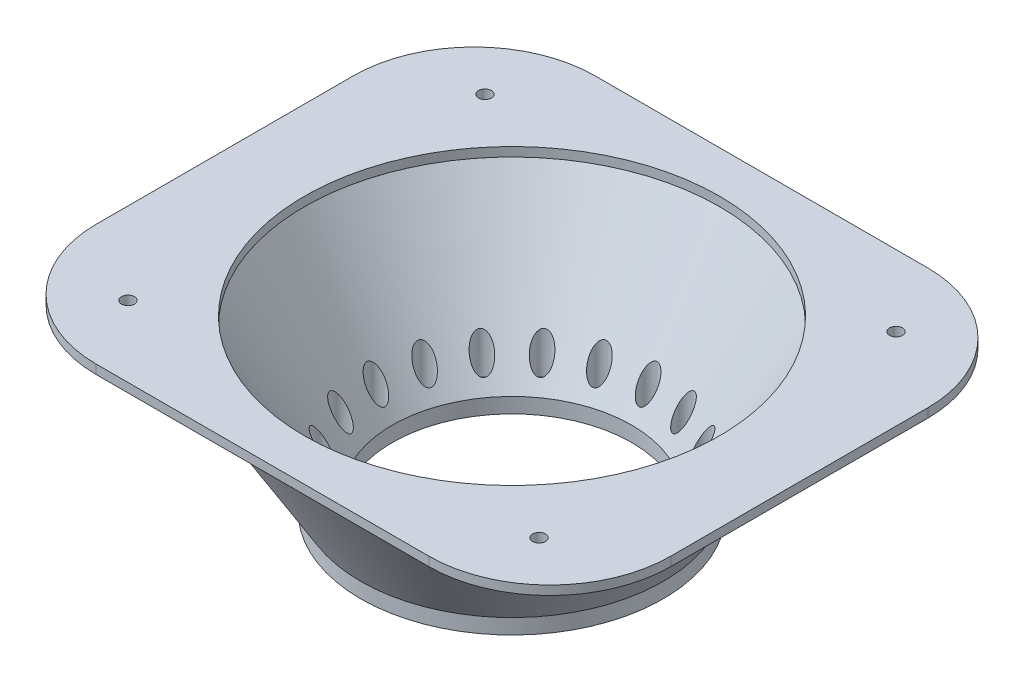
SolidWorks part; units mm, degrees
ref_plane "Front Plane" through (0, 0, 0) normal (0, 0, 1) x (1, 0, 0)
ref_plane "Top Plane" through (0, 0, 0) normal (0, 1, 0) x (1, 0, 0)
ref_plane "Right Plane" through (0, 0, 0) normal (1, 0, 0) x (0, 0, -1)
sketch "Sketch4" plane through (0, 0, 0) normal (0, 1, 0) x (1, 0, 0)
  line L0 (0, -45) -> (0, 45) construction
  line L1 (0, 0) -> (0, -45) construction
  circle A0 centre (0, 0) radius 39.565
  circle A1 centre (0, 0) radius 50
  circle A6 centre (0, -45) radius 1.75
  circle A7 centre (-13.9058, -42.7975) radius 1.75
  circle A8 centre (-26.4503, -36.4058) radius 1.75
  circle A9 centre (-36.4058, -26.4503) radius 1.75
  circle A10 centre (-42.7975, -13.9058) radius 1.75
  circle A11 centre (-45, 0) radius 1.75
  circle A12 centre (-42.7975, 13.9058) radius 1.75
  circle A13 centre (-36.4058, 26.4503) radius 1.75
  circle A14 centre (-26.4503, 36.4058) radius 1.75
  circle A15 centre (-13.9058, 42.7975) radius 1.75
  circle A16 centre (0, 45) radius 1.75
  circle A17 centre (13.9058, 42.7975) radius 1.75
  circle A18 centre (26.4503, 36.4058) radius 1.75
  circle A19 centre (36.4058, 26.4503) radius 1.75
  circle A20 centre (42.7975, 13.9058) radius 1.75
  circle A21 centre (45, 0) radius 1.75
  circle A22 centre (42.7975, -13.9058) radius 1.75
  circle A23 centre (36.4058, -26.4503) radius 1.75
  circle A24 centre (26.4503, -36.4058) radius 1.75
  circle A25 centre (13.9058, -42.7975) radius 1.75
  point P5 (0, 0)
  dimension "D1" = 79.13
  dimension "D3" = 100
  dimension "D5" = 3.5
  dimension "D2" = 90
  dimension "D7" = 45
  dimension "D6" = 20
extrude "Boss-Extrude3" add sketch "Sketch4" along normal blind 5
sketch "Sketch6" plane through (0, 0, 0) normal (1, 0, 0) x (0, 0, -1)
  line L0 (-50, 5) -> (-79.0628, 53)
  line L2 (-50, 5) -> (-39.565, 5)
  line L3 (-39.565, 5) -> (-68.6278, 53)
  line L5 (-68.6278, 53) -> (-79.0628, 53)
  point P3 (0, 0)
  dimension "D1" = 18.6278
  dimension "D2" = 48
ref_plane "Plane1" through (0, 15, 0) normal (0, 1, 0) x (1, 0, 0)
ref_axis "Axis1" through (0, 0, 0) along (0, 1, 0)
revolve "Revolve1" add sketch "Sketch6" angle 360 about axis through (0, 0, 0) along (0, 1, 0)
sketch "Sketch7" plane through (0, 53, 0) normal (0, 1, 0) x (1, 0, 0)
  line L1 (-95, 82.5) -> (95, 82.5)
  line L2 (-95, 82.5) -> (-95, -82.5)
  line L3 (-95, -82.5) -> (95, -82.5)
  line L4 (95, 82.5) -> (95, -82.5)
  line L5 (-95, 82.5) -> (95, -82.5) construction
  line L6 (-95, -82.5) -> (95, 82.5) construction
  circle A0 centre (0, 0) radius 68.6289
  circle A1 centre (-67.953, 59.0118) radius 2.15
  circle A2 centre (67.953, 59.0118) radius 2.15
  circle A3 centre (67.953, -59.0118) radius 2.15
  circle A4 centre (-67.953, -59.0118) radius 2.15
  point P4 (0, 0)
  point P16 (0, 0)
  point P17 (0, 0)
  dimension "D5" = 4.3
  dimension "D1" = 190
  dimension "D2" = 165
  dimension "D3" = 90
  dimension "D4" = 90
extrude "Boss-Extrude4" add sketch "Sketch7" along normal blind 3
fillet "Fillet1" radius 40 4 edges at (95, 54.5, -82.5) (95, 54.5, 82.5) (-95, 54.5, 82.5) (-95, 54.5, -82.5)
sketch "Sketch8" plane through (0, 0, 0) normal (0, -1, 0) x (1, 0, 0)
  line L0 (0, 0) -> (0, -45) construction
  circle A0 centre (0, -45) radius 3
  circle A1 centre (-13.9058, -42.7975) radius 3
  circle A2 centre (-26.4503, -36.4058) radius 3
  circle A3 centre (-36.4058, -26.4503) radius 3
  circle A4 centre (-42.7975, -13.9058) radius 3
  circle A5 centre (-45, 0) radius 3
  circle A6 centre (-42.7975, 13.9058) radius 3
  circle A7 centre (-36.4058, 26.4503) radius 3
  circle A8 centre (-26.4503, 36.4058) radius 3
  circle A9 centre (-13.9058, 42.7975) radius 3
  circle A10 centre (0, 45) radius 3
  circle A11 centre (13.9058, 42.7975) radius 3
  circle A12 centre (26.4503, 36.4058) radius 3
  circle A13 centre (36.4058, 26.4503) radius 3
  circle A14 centre (42.7975, 13.9058) radius 3
  circle A15 centre (45, 0) radius 3
  circle A16 centre (42.7975, -13.9058) radius 3
  circle A17 centre (36.4058, -26.4503) radius 3
  circle A18 centre (26.4503, -36.4058) radius 3
  circle A19 centre (13.9058, -42.7975) radius 3
  dimension "D1" = 20
  dimension "D3" = 6
  dimension "D2" = 45
extrude "Cut-Extrude1" cut sketch "Sketch8" against normal through all from offset 5
